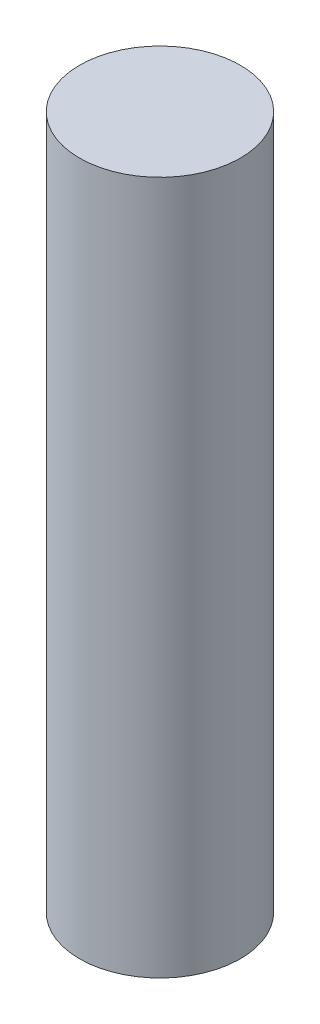
SolidWorks part; units mm, degrees
ref_plane "Front Plane" through (0, 0, 0) normal (0, 0, 1) x (1, 0, 0)
ref_plane "Top Plane" through (0, 0, 0) normal (0, 1, 0) x (1, 0, 0)
ref_plane "Right Plane" through (0, 0, 0) normal (1, 0, 0) x (0, 0, -1)
sketch "Sketch1" plane through (0, 0, 0) normal (0, 1, 0) x (1, 0, 0)
  circle A0 centre (0, 0) radius 4.9875
  dimension "D1" = 9.975
extrude "Boss-Extrude1" add sketch "Sketch1" along normal blind 43
